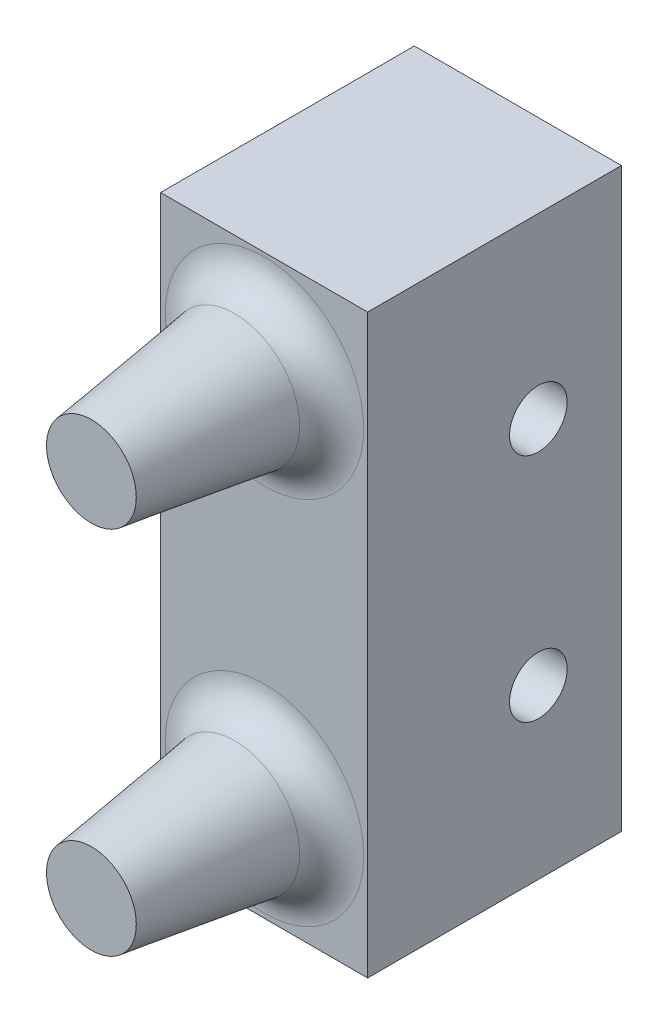
SolidWorks part; units mm, degrees
ref_plane "Front Plane" through (0, 0, 0) normal (0, 0, 1) x (1, 0, 0)
ref_plane "Top Plane" through (0, 0, 0) normal (0, 1, 0) x (1, 0, 0)
ref_plane "Right Plane" through (0, 0, 0) normal (1, 0, 0) x (0, 0, -1)
sketch "Model" plane through (0, 0, 0) normal (0, 0, 1) x (1, 0, 0)
  line L129 (715.6996, -681.0851) -> (715.6996, -649.0178)
  line L130 (697.7079, -649.0178) -> (697.7079, -681.0851)
  spline S10 degree 3 poles (697.7079, -649.0178) (697.7672, -644.0819) (701.7683, -640.0808) (706.7038, -640.0808) (711.6399, -640.0808) (715.641, -644.0819) (715.6996, -649.0178) knots 0 0 0 0 1 1 1 2 2 2 2
  spline S11 degree 3 poles (697.7079, -681.0851) (697.7079, -686.0532) (701.736, -690.0809) (706.7038, -690.0809) (711.6723, -690.0809) (715.6996, -686.0532) (715.6996, -681.0851) knots 0 0 0 0 1 1 1 2 2 2 2
sketch "Sketch2" plane through (0, 0, 0) normal (0, 0, 1) x (1, 0, 0)
  line L4 (697.7079, -649.0178) -> (697.7079, -690.0809)
  line L5 (697.7079, -690.0809) -> (715.6559, -690.0809)
  line L6 (715.6559, -690.0809) -> (715.6559, -640.0808)
  line L7 (715.6559, -640.0808) -> (697.7079, -640.0808)
  line L8 (697.7079, -640.0808) -> (697.7079, -649.0178)
  spline S0 degree 3 poles (697.7079, -681.0851) (697.7079, -686.0532) (701.736, -690.0809) (706.7038, -690.0809) (711.6723, -690.0809) (715.6996, -686.0532) (715.6996, -681.0851) knots 0 0 0 0 1 1 1 2 2 2 2 construction
  spline S1 degree 3 poles (697.7079, -649.0178) (697.7672, -644.0819) (701.7683, -640.0808) (706.7038, -640.0808) (711.6399, -640.0808) (715.641, -644.0819) (715.6996, -649.0178) knots 0 0 0 0 1 1 1 2 2 2 2 construction
extrude "Boss-Extrude1" add sketch "Sketch2" against normal blind 22
sketch "Sketch3" plane through (0, 0, 0) normal (0, 0, 1) x (1, 0, 0)
  line L0 (697.7079, -640.0808) -> (697.7079, -690.0809) construction
  circle A0 centre (706.7079, -649.0178) radius 6
  circle A1 centre (706.7079, -681.0851) radius 6
  dimension "D2" = 12
  dimension "D3" = 12
  dimension "D1" = 9
extrude "Boss-Extrude3" add sketch "Sketch3" along normal blind 15 draft 8
fillet "Fillet2" radius 3 2 edges at (712.7079, -681.0851, 0) (712.7079, -649.0178, 0)
sketch "Sketch4" plane through (715.6559, 0, 0) normal (1, 0, 0) x (0, 0, -1)
  circle A0 centre (14.8002, -655.4862) radius 2.5
extrude "Cut-Extrude1" cut sketch "Sketch4" against normal blind 50
sketch "Sketch5" plane through (715.6559, 0, 0) normal (1, 0, 0) x (0, 0, -1)
  circle A0 centre (14.8002, -675.5103) radius 2.5
extrude "Cut-Extrude2" cut sketch "Sketch5" against normal blind 50
